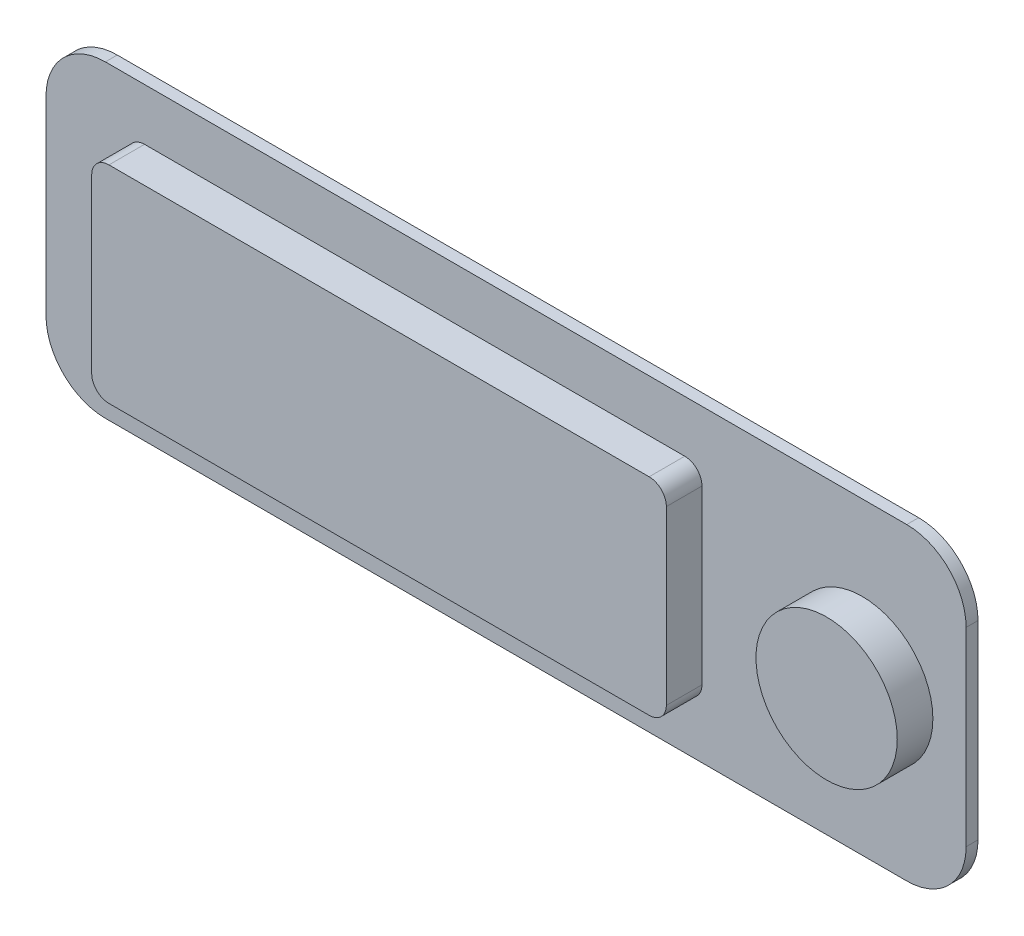
SolidWorks part; units mm, degrees
ref_plane "Plan de face" through (0, 0, 0) normal (0, 0, 1) x (1, 0, 0)
ref_plane "Plan de dessus" through (0, 0, 0) normal (0, 1, 0) x (1, 0, 0)
ref_plane "Plan de droite" through (0, 0, 0) normal (1, 0, 0) x (0, 0, -1)
sketch "Esquisse1" plane through (0, 0, 0) normal (0, 0, 1) x (1, 0, 0)
  line L1 (-48.0771, 35.5051) -> (106.9229, 35.5051)
  line L2 (-48.0771, 35.5051) -> (-48.0771, -16.4949)
  line L3 (-48.0771, -16.4949) -> (106.9229, -16.4949)
  line L4 (106.9229, 35.5051) -> (106.9229, -16.4949)
  dimension "D1" = 155
  dimension "D2" = 52
extrude "Boss.-Extru.1" add sketch "Esquisse1" along normal blind 2
fillet "Congé1" radius 10 4 edges at (-48.0771, -16.4949, 1) (106.9229, -16.4949, 1) (106.9229, 35.5051, 1) (-48.0771, 35.5051, 1)
sketch "Esquisse2" plane through (0, 0, 2) normal (0, 0, 1) x (1, 0, 0)
  line L0 (106.9229, -6.4949) -> (106.9229, 25.5051) construction
  line L2 (-31.4771, -8.0246) -> (59.5229, -8.0246)
  line L3 (-34.3771, -5.1246) -> (-34.3771, 23.8754)
  line L5 (89.4229, -27.819) -> (89.4229, 29.0479) construction
  line L6 (110.0263, 9.3754) -> (-27.8635, 9.3754) construction
  line L7 (83.6897, -8.0246) -> (-39.7736, -8.0246) construction
  line L8 (-34.3771, -27.819) -> (-34.3771, 49.5133) construction
  line L9 (62.4229, -27.819) -> (62.4229, 49.5133) construction
  line L10 (83.6897, 26.7754) -> (-39.7736, 26.7754) construction
  line L11 (-31.4771, 26.7754) -> (59.5229, 26.7754)
  line L12 (62.4229, -5.1246) -> (62.4229, 23.8754)
  circle A0 centre (89.4229, 9.3754) radius 11.9
  arc A1 (59.5229, 26.7754) -> (62.4229, 23.8754) centre (59.5229, 23.8754) cw
  arc A2 (59.5229, -8.0246) -> (62.4229, -5.1246) centre (59.5229, -5.1246) ccw
  arc A3 (-31.4771, -8.0246) -> (-34.3771, -5.1246) centre (-31.4771, -5.1246) cw
  arc A5 (-34.3771, 23.8754) -> (-31.4771, 26.7754) centre (-31.4771, 23.8754) cw
  point P17 (62.4229, 26.7754)
  point P23 (-34.3771, -8.0246)
  dimension "D6" = 2.9
  dimension "D1" = 17.5
  dimension "D2" = 96.8
  dimension "D3" = 34.8
  dimension "D4" = 17.4
  dimension "D5" = 27
extrude "Boss.-Extru.2" add sketch "Esquisse2" along normal blind 6
